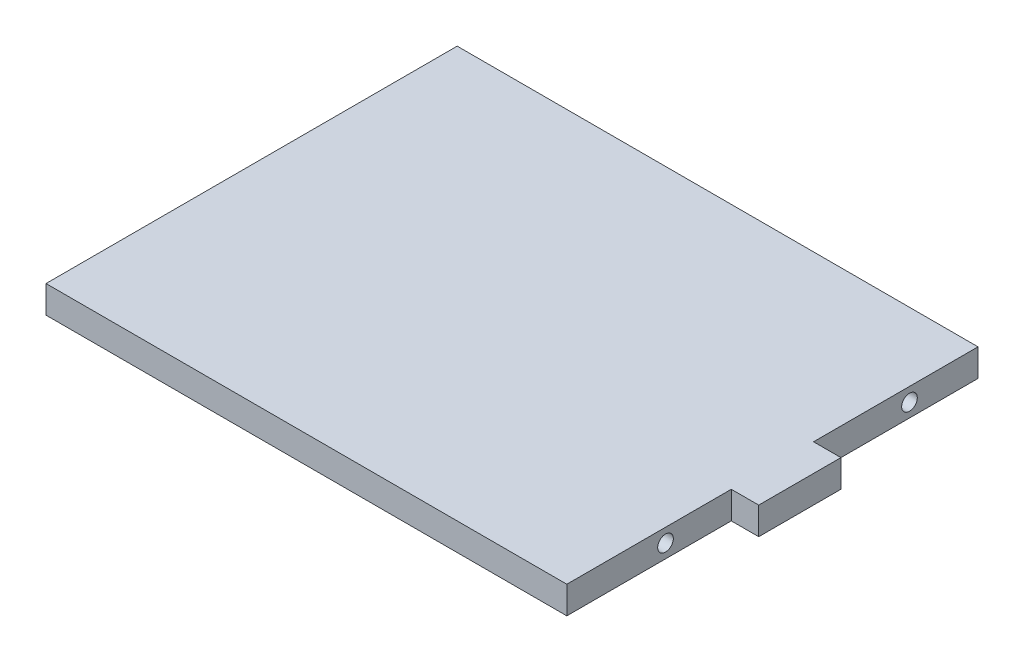
SolidWorks part; units mm, degrees
ref_plane "Front Plane" through (0, 0, 0) normal (0, 0, 1) x (1, 0, 0)
ref_plane "Top Plane" through (0, 0, 0) normal (0, 1, 0) x (1, 0, 0)
ref_plane "Right Plane" through (0, 0, 0) normal (1, 0, 0) x (0, 0, -1)
sketch "Sketch1" plane through (0, 0, 0) normal (0, 1, 0) x (1, 0, 0)
  line L1 (47.5, -37.5) -> (-47.5, -37.5)
  line L2 (47.5, -37.5) -> (47.5, 37.5)
  line L3 (47.5, 37.5) -> (-47.5, 37.5)
  line L4 (-47.5, -37.5) -> (-47.5, 37.5)
  line L5 (47.5, -37.5) -> (-47.5, 37.5) construction
  line L6 (47.5, 37.5) -> (-47.5, -37.5) construction
  point P0 (0, 0)
  dimension "D1" = 95
  dimension "D2" = 75
extrude "Boss-Extrude1" add sketch "Sketch1" along normal blind 5
sketch "Sketch3" plane through (47.5, 0, 0) normal (1, 0, 0) x (0, 0, -1)
  line L0 (-37.5, 5) -> (37.5, 5) construction
  line L1 (-7.5, 5) -> (7.5, 5)
  line L2 (-7.5, 5) -> (-7.5, 0)
  line L3 (-7.5, 0) -> (7.5, 0)
  line L4 (7.5, 5) -> (7.5, 0)
  line L5 (-37.5, 0) -> (37.5, 0) construction
  line L6 (-37.5, 5) -> (-37.5, 0) construction
  line L7 (37.5, 5) -> (37.5, 0) construction
  dimension "D1" = 30
  dimension "D2" = 30
extrude "Boss-Extrude2" add sketch "Sketch3" along normal blind 5
sketch "Sketch4" plane through (-47.5, 0, 0) normal (-1, 0, 0) x (0, 0, 1)
  circle A0 centre (-24, 2.5) radius 1.425
  circle A1 centre (13, 2.5) radius 1.4227
  dimension "D1" = 2.85
  dimension "D2" = 2.8455
extrude "Cut-Extrude1" cut sketch "Sketch4" against normal blind 25
sketch "Sketch5" plane through (47.5, 0, 0) normal (1, 0, 0) x (0, 0, -1)
  circle A0 centre (-19.5, 2.5) radius 1.425
  dimension "D1" = 2.85
extrude "Cut-Extrude2" cut sketch "Sketch5" against normal blind 25
sketch "Sketch6" plane through (47.5, 0, 0) normal (1, 0, 0) x (0, 0, -1)
  circle A0 centre (25, 2.5) radius 1.425
  dimension "D1" = 2.85
extrude "Cut-Extrude3" cut sketch "Sketch6" against normal blind 25
